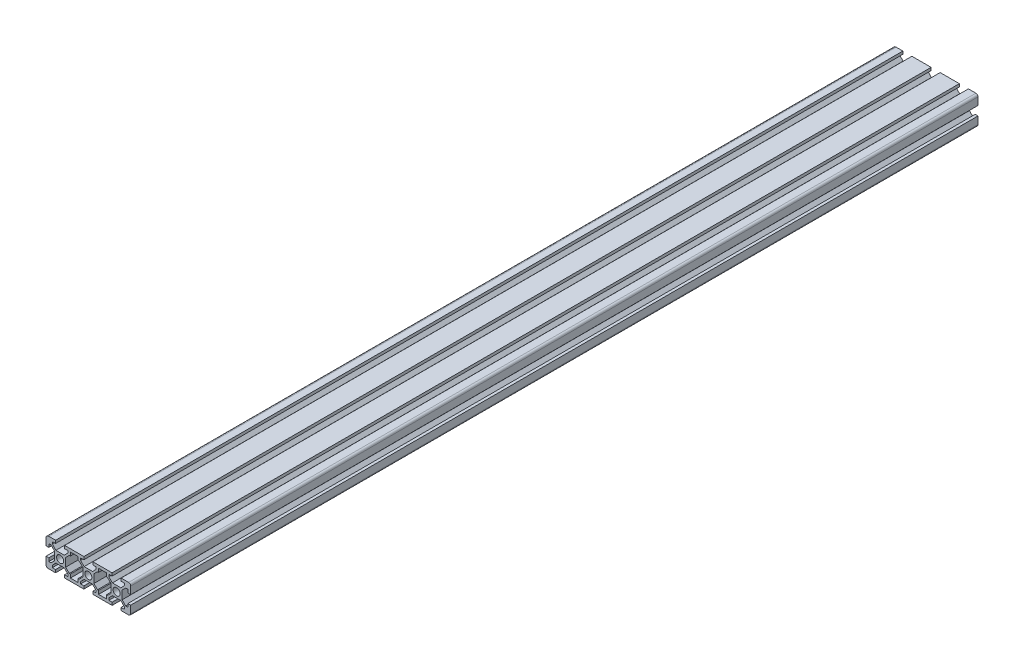
SolidWorks part; units mm, degrees
ref_plane "前视基准面" through (0, 0, 0) normal (0, 0, 1) x (1, 0, 0)
ref_plane "上视基准面" through (0, 0, 0) normal (0, 1, 0) x (1, 0, 0)
ref_plane "右视基准面" through (0, 0, 0) normal (1, 0, 0) x (0, 0, -1)
sketch "草图1" plane through (0, 0, 0) normal (0, 0, 1) x (1, 0, 0)
  line L1 (-28, 10) -> (28.5, 10)
  line L2 (-30, 8) -> (-30, -8.5)
  line L3 (-28.5, -10) -> (28.5, -10)
  line L4 (30, 8.5) -> (30, -8.5)
  line L5 (-30, 10) -> (30, -10) construction
  line L6 (-30, -10) -> (30, 10) construction
  line L7 (-30, -3.2) -> (-28, -3.2)
  line L13 (-16.8, 8) -> (-16.8, 10)
  line L14 (-14.5, 8) -> (-16.8, 8)
  line L15 (-14.5, 6.5) -> (-14.5, 8)
  line L16 (-17, 3.9) -> (-14.5, 6.5)
  line L17 (-23, 3.9) -> (-17, 3.9)
  line L18 (-25.5, 6.5) -> (-23, 3.9)
  line L25 (-28, -3.2) -> (-28, -5.5)
  line L26 (-28, -5.5) -> (-26.5, -5.5)
  line L27 (-26.5, -5.5) -> (-23.9, -3)
  line L28 (-23.9, -3) -> (-23.9, 3)
  line L29 (-23.9, 3) -> (-26.5, 5.5)
  line L30 (-26.5, 5.5) -> (-28, 5.5)
  line L31 (-28, 5.5) -> (-28, 3.2)
  line L32 (-28, 3.2) -> (-30, 3.2)
  line L33 (-25.5, 8) -> (-25.5, 6.5)
  line L34 (-23.2, 8) -> (-25.5, 8)
  line L35 (-23.2, 10) -> (-23.2, 8)
  line L36 (-12, -3.2) -> (-8, -3.2)
  line L37 (-12, -5.5) -> (-12, -3.2)
  line L38 (-13.5, -5.5) -> (-12, -5.5)
  line L39 (-16.1, -3) -> (-13.5, -5.5)
  line L40 (-16.1, 3) -> (-16.1, -3)
  line L41 (-13.5, 5.5) -> (-16.1, 3)
  line L42 (-12, 5.5) -> (-13.5, 5.5)
  line L43 (-12, 3.2) -> (-12, 5.5)
  line L44 (-8, 3.2) -> (-12, 3.2)
  line L45 (-23.2, -8) -> (-23.2, -10)
  line L46 (-25.5, -8) -> (-23.2, -8)
  line L47 (-25.5, -6.5) -> (-25.5, -8)
  line L48 (-23, -3.9) -> (-25.5, -6.5)
  line L49 (-17, -3.9) -> (-23, -3.9)
  line L50 (-14.5, -6.5) -> (-17, -3.9)
  line L51 (-14.5, -8) -> (-14.5, -6.5)
  line L52 (-16.8, -8) -> (-14.5, -8)
  line L53 (-16.8, -10) -> (-16.8, -8)
  line L54 (-10, 3.2) -> (-10, -3.2) construction
  line L55 (-10, -3.2) -> (-10, 3.2) construction
  line L56 (3, 3.9) -> (-3, 3.9)
  line L57 (5.5, 6.5) -> (3, 3.9)
  line L58 (5.5, 8) -> (5.5, 6.5)
  line L59 (3.2, 8) -> (5.5, 8)
  line L60 (3.2, 10) -> (3.2, 8)
  line L61 (-3.2, 8) -> (-3.2, 10)
  line L62 (-5.5, 8) -> (-3.2, 8)
  line L63 (-5.5, 6.5) -> (-5.5, 8)
  line L64 (-3, 3.9) -> (-5.5, 6.5)
  line L65 (-6.5, 5.5) -> (-3.9, 3)
  line L66 (-8, 5.5) -> (-6.5, 5.5)
  line L67 (-8, 3.2) -> (-8, 5.5)
  line L68 (-8, -5.5) -> (-8, -3.2)
  line L69 (-6.5, -5.5) -> (-8, -5.5)
  line L70 (-3.9, -3) -> (-6.5, -5.5)
  line L71 (-3.9, 3) -> (-3.9, -3)
  line L72 (-3, -3.9) -> (3, -3.9)
  line L73 (-5.5, -6.5) -> (-3, -3.9)
  line L74 (-5.5, -8) -> (-5.5, -6.5)
  line L75 (-3.2, -8) -> (-5.5, -8)
  line L76 (-3.2, -10) -> (-3.2, -8)
  line L77 (3.2, -8) -> (3.2, -10)
  line L78 (5.5, -8) -> (3.2, -8)
  line L79 (5.5, -6.5) -> (5.5, -8)
  line L80 (3, -3.9) -> (5.5, -6.5)
  line L81 (3.9, -3) -> (3.9, 3)
  line L82 (6.5, -5.5) -> (3.9, -3)
  line L83 (8, -5.5) -> (6.5, -5.5)
  line L84 (8, -3.2) -> (8, -5.5)
  line L85 (12, -3.2) -> (8, -3.2)
  line L86 (8, 3.2) -> (12, 3.2)
  line L87 (8, 5.5) -> (8, 3.2)
  line L88 (6.5, 5.5) -> (8, 5.5)
  line L89 (3.9, 3) -> (6.5, 5.5)
  line L90 (10, 3.2) -> (10, -3.133) construction
  line L91 (23.2, 8) -> (23.2, 10)
  line L92 (25.5, 8) -> (23.2, 8)
  line L93 (25.5, 6.5) -> (25.5, 8)
  line L94 (23, 3.9) -> (25.5, 6.5)
  line L95 (17, 3.9) -> (23, 3.9)
  line L96 (16.8, 10) -> (16.8, 8)
  line L97 (16.8, 8) -> (14.5, 8)
  line L98 (14.5, 8) -> (14.5, 6.5)
  line L99 (14.5, 6.5) -> (17, 3.9)
  line L100 (16.1, 3) -> (13.5, 5.5)
  line L101 (13.5, 5.5) -> (12, 5.5)
  line L102 (12, 5.5) -> (12, 3.2)
  line L103 (12, -3.2) -> (12, -5.5)
  line L104 (12, -5.5) -> (13.5, -5.5)
  line L105 (16.1, -3) -> (16.1, 3)
  line L106 (13.5, -5.5) -> (16.1, -3)
  line L107 (17, -3.9) -> (14.5, -6.5)
  line L108 (14.5, -6.5) -> (14.5, -8)
  line L109 (14.5, -8) -> (16.8, -8)
  line L110 (16.8, -8) -> (16.8, -10)
  line L111 (23.2, -10) -> (23.2, -8)
  line L112 (23.2, -8) -> (25.5, -8)
  line L113 (25.5, -8) -> (25.5, -6.5)
  line L114 (25.5, -6.5) -> (23, -3.9)
  line L115 (23, -3.9) -> (17, -3.9)
  line L116 (28, 3.2) -> (30, 3.2)
  line L117 (30, -3.2) -> (28, -3.2)
  line L118 (28, -5.5) -> (28, -3.2)
  line L119 (26.5, -5.5) -> (28, -5.5)
  line L120 (23.9, -3) -> (26.5, -5.5)
  line L121 (23.9, 3) -> (23.9, -3)
  line L122 (26.5, 5.5) -> (23.9, 3)
  line L123 (28, 5.5) -> (26.5, 5.5)
  line L124 (28, 3.2) -> (28, 5.5)
  line L125 (-12.75, 5.5) -> (-12.75, 8)
  line L126 (-7.25, 5.5) -> (-7.25, 8)
  line L127 (-7.25, 8) -> (-12.75, 8)
  line L128 (-12.75, -5.5) -> (-12.75, -8)
  line L129 (-7.25, -5.5) -> (-7.25, -8)
  line L130 (-7.25, -8) -> (-12.75, -8)
  line L131 (7.25, 5.5) -> (7.25, 8)
  line L132 (12.75, 5.5) -> (12.75, 8)
  line L133 (12.75, 8) -> (7.25, 8)
  line L134 (7.25, -5.5) -> (7.25, -8)
  line L135 (12.75, -5.5) -> (12.75, -8)
  line L136 (12.75, -8) -> (7.25, -8)
  circle A0 centre (0, 0) radius 2.5
  circle A1 centre (-20, 0) radius 2.5
  circle A2 centre (20, 0) radius 2.5
  arc A3 (-30, 8) -> (-28, 10) centre (-28, 8) cw
  arc A4 (-30, -8.5) -> (-28.5, -10) centre (-28.5, -8.5) ccw
  arc A5 (28.5, -10) -> (30, -8.5) centre (28.5, -8.5) ccw
  arc A6 (30, 8.5) -> (28.5, 10) centre (28.5, 8.5) ccw
  point P0 (0, 0)
  point P63 (-20, 0)
  point P115 (10, -3.2)
  dimension "D1" = 20
  dimension "D7" = 5
  dimension "D8" = 5
  dimension "D9" = 5
  dimension "D5" = 2
  dimension "D6" = 1.5
  dimension "D12" = 1.5
  dimension "D2" = 20
  dimension "D3" = 60
  dimension "D4" = 20
  dimension "D10" = 6.1
  dimension "D11" = 2.3
  dimension "D14" = 6.4
  dimension "D15" = 13.2
  dimension "D16" = 11
  dimension "D17" = 10
  dimension "D18" = 6
  dimension "D19" = 1.5
  dimension "D20" = 2
  dimension "D21" = 2
  dimension "D22" = 1.5
  dimension "D23" = 7
  dimension "D24" = 4
extrude "凸台-拉伸2" add sketch "草图1" along normal blind 600 contours L4 A6 L1 L91 L92 L93 L94 L95 L99 L98 L97 L96 L60 L59 L58 L57 L56 L64 L63 L62 L61 L13 L14 L15 L16 L17 L18 L33 L34 L35 A3 L2 L32 L31 L30 L29 L28 L27 L26 L25 L7 A4 L3 L45 L46 L47 L48
